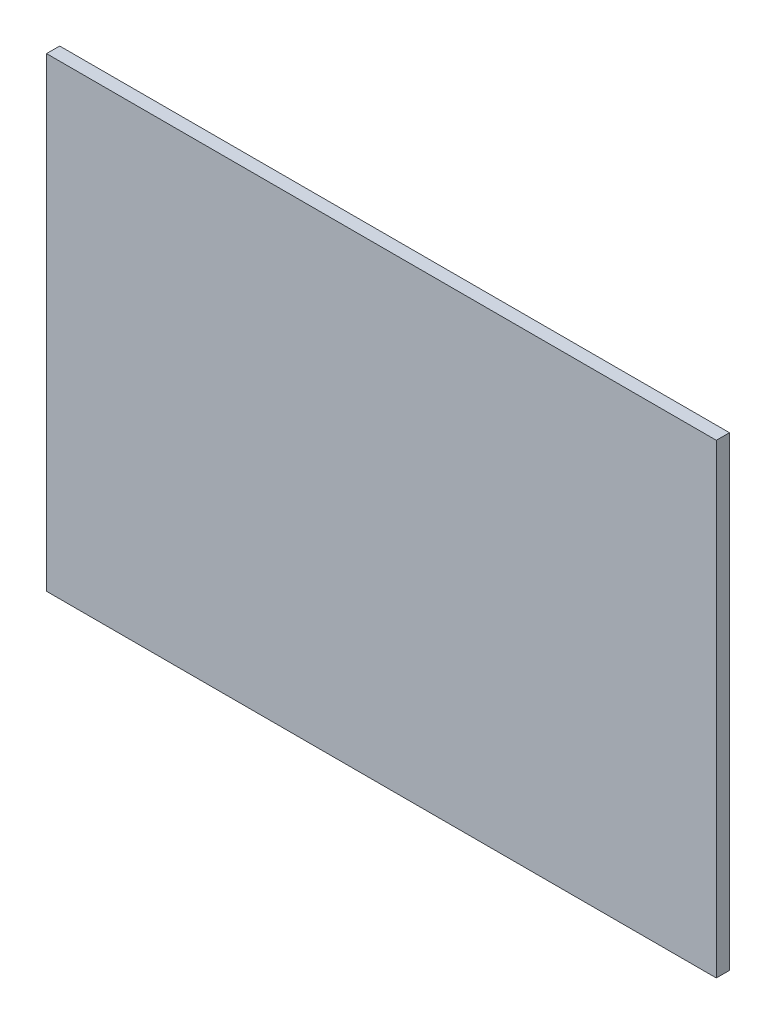
SolidWorks part; units mm, degrees
ref_plane "Front Plane" through (0, 0, 0) normal (0, 0, 1) x (1, 0, 0)
ref_plane "Top Plane" through (0, 0, 0) normal (0, 1, 0) x (1, 0, 0)
ref_plane "Right Plane" through (0, 0, 0) normal (1, 0, 0) x (0, 0, -1)
sketch "Sketch1" plane through (0, 0, 0) normal (0, 0, 1) x (1, 0, 0)
  line L1 (-200.6578, 58.498) -> (-45.3528, 58.498)
  line L2 (-200.6578, 58.498) -> (-200.6578, 170.893)
  line L3 (-200.6578, 170.893) -> (-45.3528, 170.893)
  line L4 (-45.3528, 58.498) -> (-45.3528, 170.893)
extrude "Boss-Extrude1" add sketch "Sketch1" along normal blind 3.175
sketch "Sketch2" plane through (-200.6578, 0, 0) normal (-1, 0, 0) x (0, 0, 1)
  line L1 (0, 170.893) -> (3.175, 170.893)
  line L2 (0, 170.893) -> (0, 58.498)
  line L3 (0, 58.498) -> (3.175, 58.498)
  line L4 (3.175, 170.893) -> (3.175, 58.498)
extrude "Boss-Extrude2" add sketch "Sketch2" along normal blind 6.35
